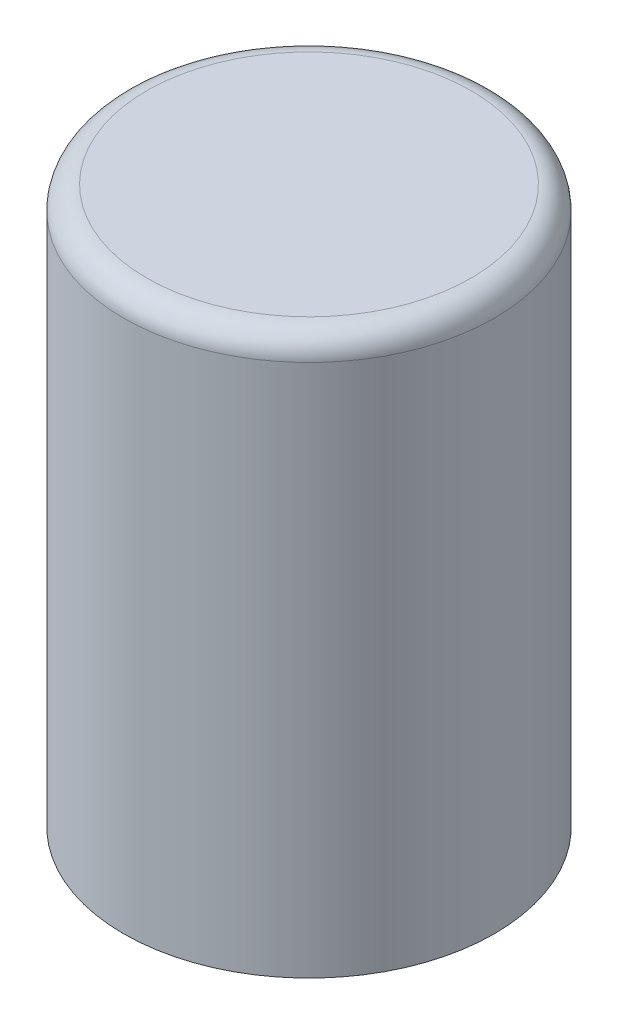
SolidWorks part; units mm, degrees
ref_plane "Front Plane" through (0, 0, 0) normal (0, 0, 1) x (1, 0, 0)
ref_plane "Top Plane" through (0, 0, 0) normal (0, 1, 0) x (1, 0, 0)
ref_plane "Right Plane" through (0, 0, 0) normal (1, 0, 0) x (0, 0, -1)
sketch "Sketch1" plane through (0, 0, 0) normal (0, 1, 0) x (1, 0, 0)
  circle A0 centre (0, 0) radius 2
  dimension "D1" = 4
extrude "Boss-Extrude1" add sketch "Sketch1" along normal blind 6
fillet "Fillet1" radius 0.25 1 edges at (0, 6, 2)
